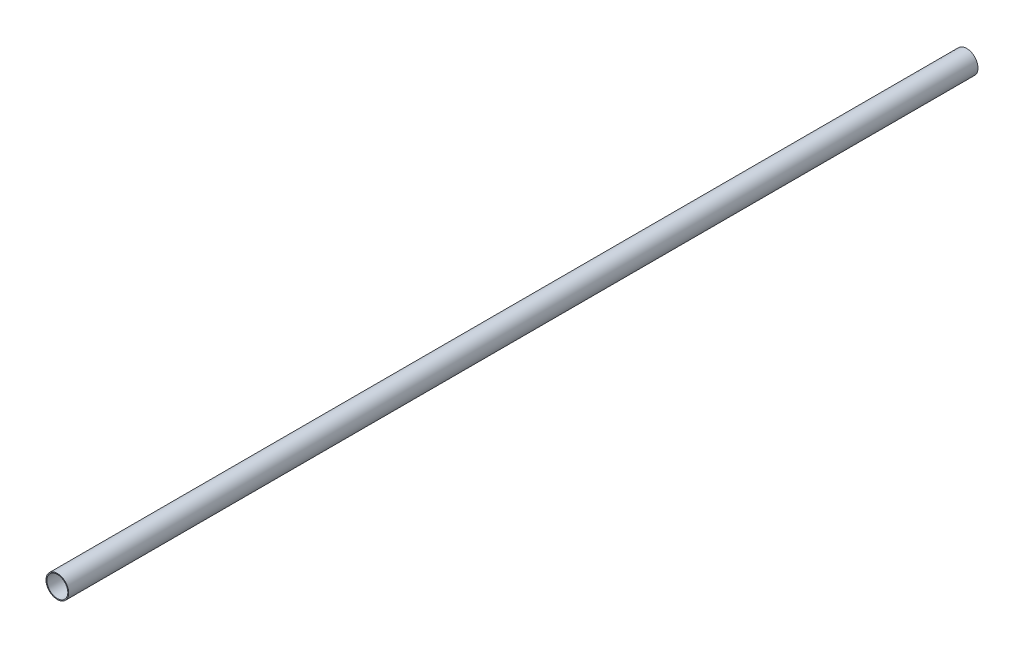
SolidWorks part; units mm, degrees
ref_plane "Front Plane" through (0, 0, 0) normal (0, 0, 1) x (1, 0, 0)
ref_plane "Top Plane" through (0, 0, 0) normal (0, 1, 0) x (1, 0, 0)
ref_plane "Right Plane" through (0, 0, 0) normal (1, 0, 0) x (0, 0, -1)
sketch "Sketch1" plane through (0, 0, 0) normal (0, 0, 1) x (1, 0, 0)
  circle A0 centre (0, 0) radius 12.5
  circle A1 centre (0, 0) radius 11.5
  dimension "D1" = 25
  dimension "D2" = 1
extrude "Boss-Extrude2" add sketch "Sketch1" along normal blind 1000
